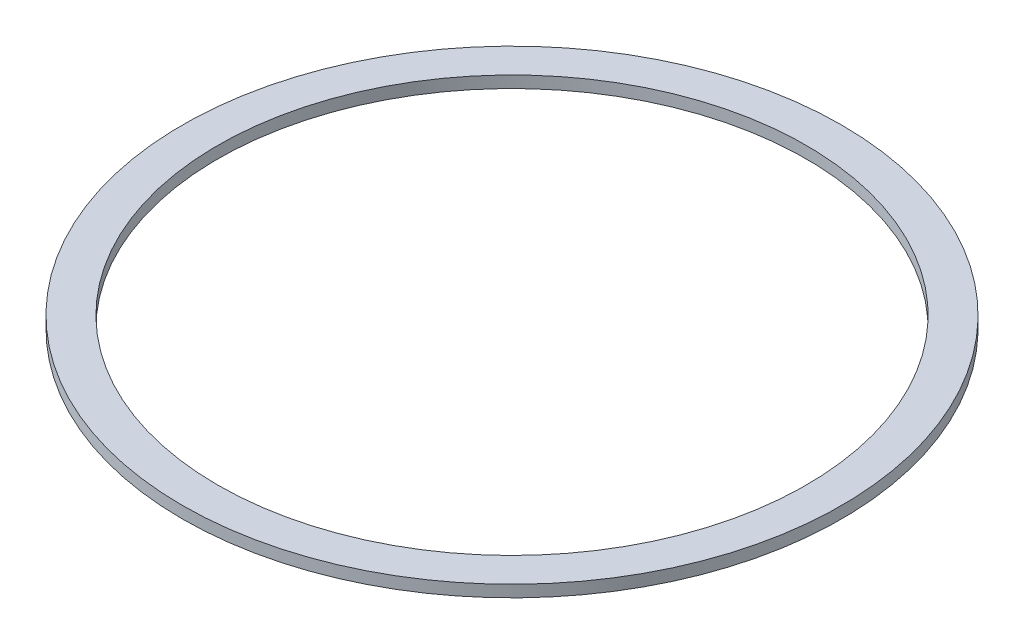
SolidWorks part; units mm, degrees
material "Thornel Mat VMA"
ref_plane "前视基准面" through (0, 0, 0) normal (0, 0, 1) x (1, 0, 0)
ref_plane "上视基准面" through (0, 0, 0) normal (0, 1, 0) x (1, 0, 0)
ref_plane "右视基准面" through (0, 0, 0) normal (1, 0, 0) x (0, 0, -1)
sketch "草图1" plane through (0, 0, 0) normal (0, 1, 0) x (1, 0, 0)
  circle A0 centre (0, 0) radius 28
  circle A1 centre (0, 0) radius 25
  dimension "D1" = 50
  dimension "D2" = 3
extrude "凸台-拉伸1" add sketch "草图1" along normal blind 1
